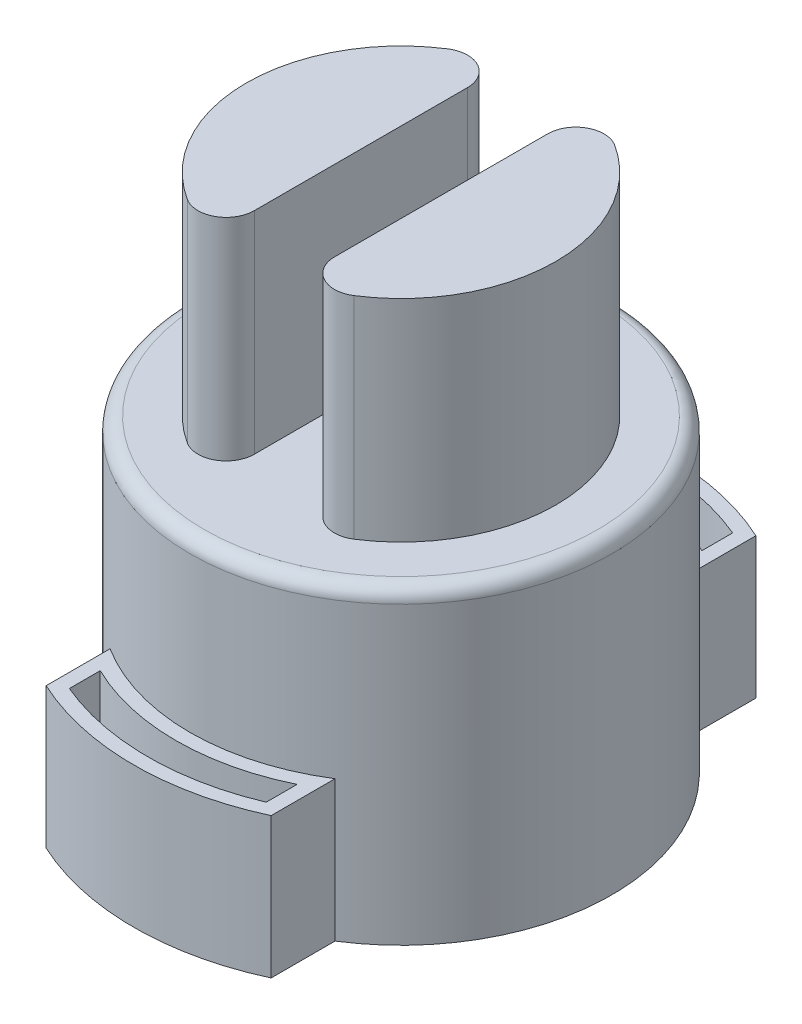
SolidWorks part; units mm, degrees
ref_plane "Front Plane" through (0, 0, 0) normal (0, 0, 1) x (1, 0, 0)
ref_plane "Top Plane" through (0, 0, 0) normal (0, 1, 0) x (1, 0, 0)
ref_plane "Right Plane" through (0, 0, 0) normal (1, 0, 0) x (0, 0, -1)
sketch "Sketch1" plane through (0, 0, 0) normal (0, 1, 0) x (1, 0, 0)
  circle A0 centre (0, 0) radius 15
  dimension "D1" = 30
extrude "Boss-Extrude1" add sketch "Sketch1" against normal blind 20
sketch "Sketch2" plane through (0, 0, 0) normal (0, 1, 0) x (1, 0, 0)
  circle A0 centre (0, 0) radius 11
  dimension "D1" = 22
extrude "Boss-Extrude2" add sketch "Sketch2" along normal blind 15 contours A0
sketch "Sketch3" plane through (0, 15, 0) normal (0, 1, 0) x (1, 0, 0)
  line L1 (-2.85, 12) -> (2.85, 12)
  line L2 (-2.85, 12) -> (-2.85, -12)
  line L3 (-2.85, -12) -> (2.85, -12)
  line L4 (2.85, 12) -> (2.85, -12)
  dimension "D1" = 5.7
  dimension "D2" = 2.85
  dimension "D3" = 12
  dimension "D4" = 24
extrude "Cut-Extrude1" cut sketch "Sketch3" against normal blind 15
fillet "Fillet3" radius 1 1 edges at (0, 0, 15)
fillet "Fillet4" radius 2 4 edges at (-2.85, 7.5, 10.6244) (-2.85, 7.5, -10.6244) (2.85, 7.5, -10.6244) (2.85, 7.5, 10.6244)
sketch "Sketch4" plane through (0, -20, 0) normal (0, -1, 0) x (1, 0, 0)
  line L1 (-8, 20) -> (8, 20)
  line L2 (-8, 20) -> (-8, -20)
  line L3 (-8, -20) -> (8, -20)
  line L4 (8, 20) -> (8, -20)
  circle A0 centre (0, 0) radius 19
  circle M6 centre (0, 0) radius 15
  dimension "D1" = 38
  dimension "D2" = 40
  dimension "D3" = 20
  dimension "D4" = 16
  dimension "D5" = 8
extrude "Boss-Extrude3" add sketch "Sketch4" along normal blind 2 contours L4 L2 M6 | L4 A0 L2 M6 | L2 M6 | L4 M6 | L2 A0 L4 M6
sketch "Sketch7" plane through (0, -22, 0) normal (0, -1, 0) x (1, 0, 0)
  line L1 (-8, -20) -> (8, -20)
  line L2 (-8, -20) -> (-8, 20)
  line L3 (-8, 20) -> (8, 20)
  line L4 (8, -20) -> (8, 20)
  circle A0 centre (0, 0) radius 19
  circle A1 centre (0, 0) radius 15
  line M7 (8, -17.2337) -> (8, -12.6886)
  line M9 (8, 12.6886) -> (8, 17.2337)
  arc M10 (8, 17.2337) -> (-8, 17.2337) centre (0, 0) ccw
  line M11 (-8, 17.2337) -> (-8, 12.6886)
  line M13 (-8, -12.6886) -> (-8, -17.2337)
  arc M14 (-8, -17.2337) -> (8, -17.2337) centre (0, 0) ccw
  dimension "D1" = 38
  dimension "D2" = 30
  dimension "D3" = 16
  dimension "D4" = 20
  dimension "D5" = 40
  dimension "D6" = 8
extrude "Boss-Extrude4" add sketch "Sketch7" against normal blind 10 contours A1 M13 M14 M7 | A1 M9 M10 M11
sketch "Sketch8" plane through (0, -12, 0) normal (0, 1, 0) x (1, 0, 0)
  line L4 (7, 14.3875) -> (7, 16.5831)
  line L5 (-7, 16.5831) -> (-7, 14.3875)
  line L6 (7, 14.3875) -> (7, 16.5831)
  line L7 (-7, 16.5831) -> (-7, 14.3875)
  arc A4 (7, 16.5831) -> (-7, 16.5831) centre (0, 0) ccw
  arc A5 (7, 14.3875) -> (-7, 14.3875) centre (0, 0) ccw
  arc A6 (7, 16.5831) -> (-7, 16.5831) centre (0, 0) ccw
  arc A7 (7, 14.3875) -> (-7, 14.3875) centre (0, 0) ccw
  dimension "D1" = 1
extrude "Cut-Extrude2" cut sketch "Sketch8" against normal blind 11
sketch "Sketch9" plane through (0, -12, 0) normal (0, 1, 0) x (1, 0, 0)
  line L4 (-7, -14.3875) -> (-7, -16.5831)
  line L5 (7, -16.5831) -> (7, -14.3875)
  line L6 (-7, -14.3875) -> (-7, -16.5831)
  line L7 (7, -16.5831) -> (7, -14.3875)
  arc A4 (-7, -14.3875) -> (7, -14.3875) centre (0, 0) ccw
  arc A5 (-7, -16.5831) -> (7, -16.5831) centre (0, 0) ccw
  arc A6 (-7, -14.3875) -> (7, -14.3875) centre (0, 0) ccw
  arc A7 (-7, -16.5831) -> (7, -16.5831) centre (0, 0) ccw
  dimension "D1" = 1
extrude "Cut-Extrude3" cut sketch "Sketch9" against normal blind 11
